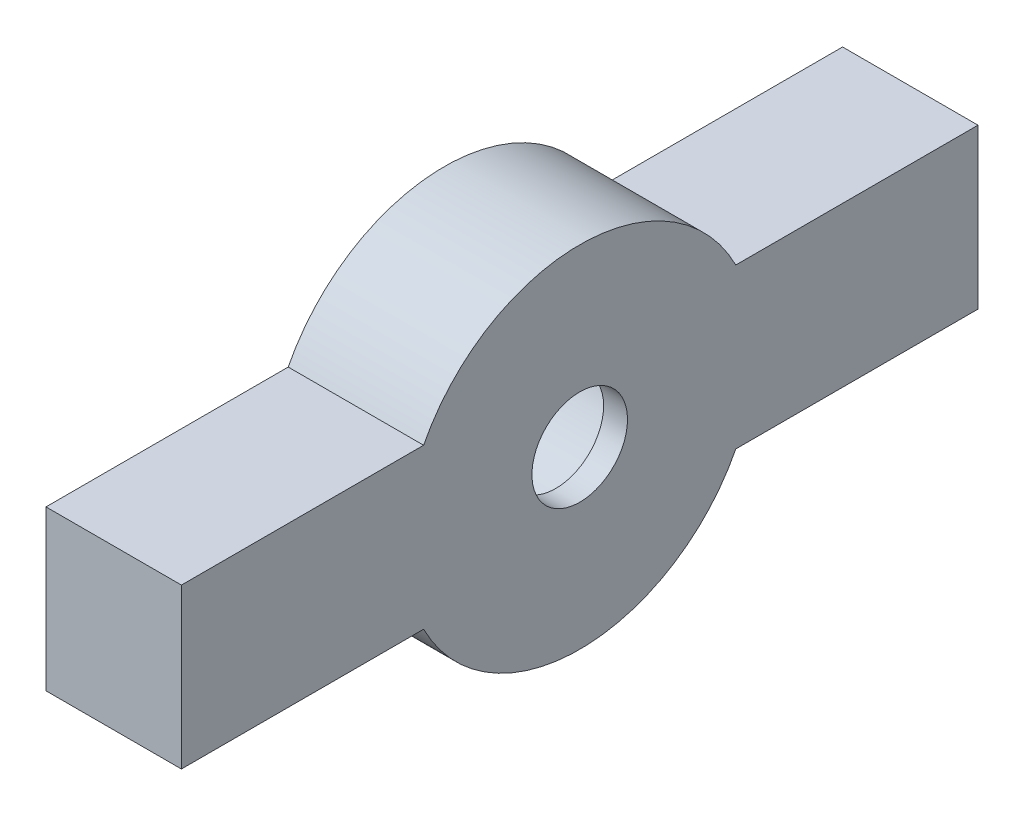
SolidWorks part; units mm, degrees
ref_plane "前视基准面" through (0, 0, 0) normal (0, 0, 1) x (1, 0, 0)
ref_plane "上视基准面" through (0, 0, 0) normal (0, 1, 0) x (1, 0, 0)
ref_plane "右视基准面" through (0, 0, 0) normal (1, 0, 0) x (0, 0, -1)
sketch "草图1" plane through (0, 0, 0) normal (1, 0, 0) x (0, 0, -1)
  line L1 (10, 2) -> (-10, 2)
  line L2 (10, 2) -> (10, -2)
  line L3 (10, -2) -> (-10, -2)
  line L4 (-10, 2) -> (-10, -2)
  line L5 (10, 2) -> (-10, -2) construction
  line L6 (10, -2) -> (-10, 2) construction
  circle A0 centre (0, 0) radius 2.4
  circle A1 centre (0, 0) radius 4.4
  dimension "D1" = 4.8
  dimension "D2" = 2
  dimension "D3" = 20
  dimension "D4" = 4
extrude "凸台-拉伸1" add sketch "草图1" along normal blind 3.4 contours L1 A1 A0 | L3 A1 L1 A0 | L1 A1 L3 A0 | A1 L1 L4 L3 | A1 L3 L2 L1 | L3 A1 A0
sketch "草图2" plane through (3.4, 0, 0) normal (1, 0, 0) x (0, 0, -1)
  circle A0 centre (0, 0) radius 1.2
  circle A1 centre (0, 0) radius 2.4 construction
  circle A2 centre (0, 0) radius 2.4
  dimension "D1" = 2.4
extrude "凸台-拉伸2" add sketch "草图2" against normal blind 0.6
chamfer "倒角1" distance 0.2 angle 45 1 edges at (0, 0, -2.4)
